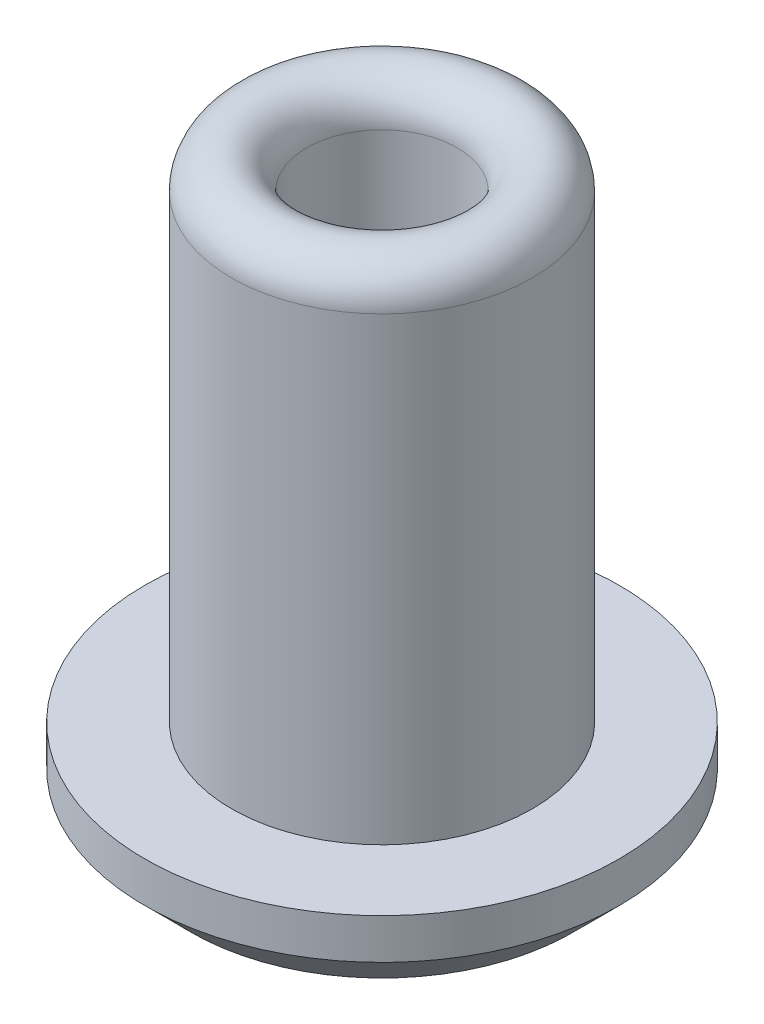
SolidWorks part; units mm, degrees
material "ABS PC"
ref_plane "Front Plane" through (0, 0, 0) normal (0, 0, 1) x (1, 0, 0)
ref_plane "Top Plane" through (0, 0, 0) normal (0, 1, 0) x (1, 0, 0)
ref_plane "Right Plane" through (0, 0, 0) normal (1, 0, 0) x (0, 0, -1)
sketch "Sketch1" plane through (0, 0, 0) normal (0, 0, 1) x (1, 0, 0)
  line L0 (0, -1000) -> (0, 49000) construction
  line L1 (0, 0) -> (0, 0.5)
  line L3 (-2.6, 9.45) -> (-2.6, 1.5)
  line L4 (-2.6, 1.5) -> (-4.1, 1.5)
  line L5 (-4.1, 1.5) -> (-4.1, 0)
  line L6 (-4.1, 0) -> (0, 0)
  line L7 (-1.3, 9.45) -> (-1.3, 1.5)
  line L8 (-0.3, 0.5) -> (0, 0.5)
  arc A0 (-1.3, 1.5) -> (-0.3, 0.5) centre (-0.3, 1.5) ccw
  arc A1 (-2.6, 9.45) -> (-1.3, 9.45) centre (-1.95, 9.45) cw
  point P14 (-1.95, 10.1)
  dimension "D6" = 1
  dimension "D1" = 5.2
  dimension "D2" = 8.6
  dimension "D3" = 1.5
  dimension "D4" = 1.5
  dimension "D5" = 0.5
  dimension "D7" = 2.6
revolve "Revolve1" add sketch "Sketch1" angle 360 about L0
chamfer "Chamfer1" distance 0.8 angle 45 1 edges at (4.1, 0, 0)
